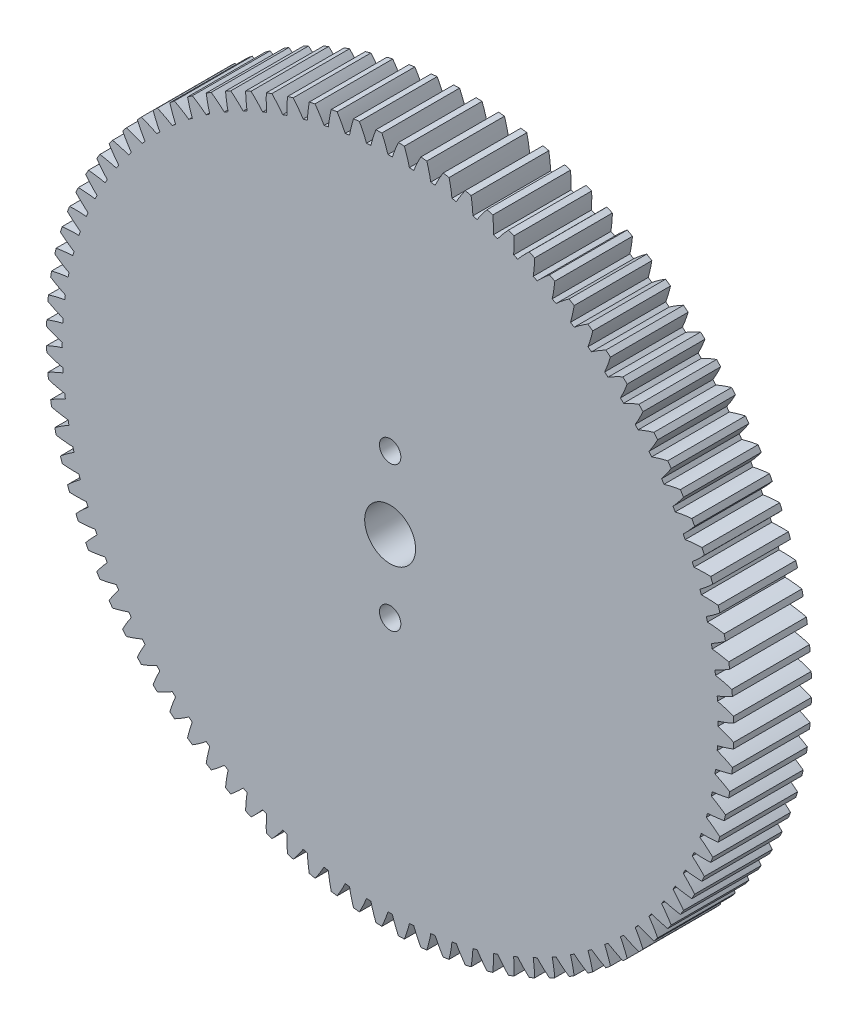
SolidWorks part; units mm, degrees
ref_plane "Front Plane" through (0, 0, 0) normal (0, 0, 1) x (1, 0, 0)
ref_plane "Top Plane" through (0, 0, 0) normal (0, 1, 0) x (1, 0, 0)
ref_plane "Right Plane" through (0, 0, 0) normal (1, 0, 0) x (0, 0, -1)
sketch "Model" plane through (0, 0, 0) normal (0, 0, 1) x (1, 0, 0)
  arc A0 (41.8739, 5.2281) -> (41.8002, 5.7878) centre (0, 0) ccw
  arc A1 (41.8002, 5.7878) -> (43.6952, 6.8252) centre (34.4061, 21.5441) ccw
  arc A2 (43.6952, 6.8252) -> (43.5702, 7.5824) centre (0, 0) ccw
  circle A387 centre (0, -9.3) radius 1.375
  circle A388 centre (0, 9.3) radius 1.375
  circle A389 centre (0, 0) radius 3.275
  arc A390 (43.5702, 7.5824) -> (41.4423, 7.9556) centre (39.5053, -9.3413) ccw
  arc A391 (41.4423, 7.9556) -> (41.3322, 8.5093) centre (0, 0) ccw
  arc A392 (41.3322, 8.5093) -> (43.1552, 9.6684) centre (32.9234, 23.7483) ccw
  arc A393 (43.1552, 9.6684) -> (42.981, 10.4158) centre (0, 0) ccw
  arc A394 (42.981, 10.4158) -> (40.8333, 10.649) centre (40.0317, -6.7375) ccw
  arc A395 (40.8333, 10.649) -> (40.6871, 11.1943) centre (0, 0) ccw
  arc A396 (40.6871, 11.1943) -> (42.4305, 12.4702) centre (31.2997, 25.8507) ccw
  arc A397 (42.4305, 12.4702) -> (42.2077, 13.2046) centre (0, 0) ccw
  arc A398 (42.2077, 13.2046) -> (40.0493, 13.2968) centre (40.3866, -4.1049) ccw
  arc A399 (40.0493, 13.2968) -> (39.8679, 13.8314) centre (0, 0) ccw
  arc A400 (39.8679, 13.8314) -> (41.5241, 15.2185) centre (29.542, 27.8425) ccw
  arc A401 (41.5241, 15.2185) -> (41.2537, 15.9368) centre (0, 0) ccw
  arc A402 (41.2537, 15.9368) -> (39.0939, 15.8877) centre (40.5686, -1.4547) ccw
  arc A403 (39.0939, 15.8877) -> (38.8779, 16.4093) centre (0, 0) ccw
  arc A404 (38.8779, 16.4093) -> (40.4398, 17.9018) centre (27.6577, 29.715) ccw
  arc A405 (40.4398, 17.9018) -> (40.1231, 18.6008) centre (0, 0) ccw
  arc A406 (40.1231, 18.6008) -> (37.9711, 18.4106) centre (40.5769, 1.2017) ccw
  arc A407 (37.9711, 18.4106) -> (37.7214, 18.9169) centre (0, 0) ccw
  arc A408 (37.7214, 18.9169) -> (39.1824, 20.5083) centre (25.6551, 31.4603) ccw
  arc A409 (39.1824, 20.5083) -> (38.8206, 21.1852) centre (0, 0) ccw
  arc A410 (38.8206, 21.1852) -> (36.6857, 20.8546) centre (40.4115, 3.853) ccw
  arc A411 (36.6857, 20.8546) -> (36.4034, 21.3435) centre (0, 0) ccw
  arc A412 (36.4034, 21.3435) -> (37.7572, 23.0271) centre (23.5425, 33.0708) ccw
  arc A413 (37.7572, 23.0271) -> (37.3519, 23.6788) centre (0, 0) ccw
  arc A414 (37.3519, 23.6788) -> (35.2432, 23.2093) centre (40.0729, 6.4878) ccw
  arc A415 (35.2432, 23.2093) -> (34.9296, 23.6787) centre (0, 0) ccw
  arc A416 (34.9296, 23.6787) -> (36.1703, 25.4472) centre (21.3292, 34.5398) ccw
  arc A417 (36.1703, 25.4472) -> (35.7233, 26.071) centre (0, 0) ccw
  arc A418 (35.7233, 26.071) -> (33.6498, 25.4646) centre (39.5628, 9.0948) ccw
  arc A419 (33.6498, 25.4646) -> (33.3061, 25.9125) centre (0, 0) ccw
  arc A420 (33.3061, 25.9125) -> (34.4285, 27.7584) centre (19.0245, 35.8608) ccw
  arc A421 (34.4285, 27.7584) -> (33.9417, 28.3516) centre (0, 0) ccw
  arc A422 (33.9417, 28.3516) -> (31.9123, 27.6109) centre (38.8833, 11.6629) ccw
  arc A423 (31.9123, 27.6109) -> (31.5401, 28.0353) centre (0, 0) ccw
  arc A424 (31.5401, 28.0353) -> (32.5393, 29.9507) centre (16.6384, 37.0283) ccw
  arc A425 (32.5393, 29.9507) -> (32.0147, 30.5108) centre (0, 0) ccw
  arc A426 (32.0147, 30.5108) -> (30.0381, 29.6389) centre (38.0372, 14.181) ccw
  arc A427 (30.0381, 29.6389) -> (29.6389, 30.0381) centre (0, 0) ccw
  arc A428 (29.6389, 30.0381) -> (30.5108, 32.0147) centre (14.181, 38.0372) ccw
  arc A429 (30.5108, 32.0147) -> (29.9507, 32.5393) centre (0, 0) ccw
  arc A430 (29.9507, 32.5393) -> (28.0353, 31.5401) centre (37.0283, 16.6384) ccw
  arc A431 (28.0353, 31.5401) -> (27.6109, 31.9123) centre (0, 0) ccw
  arc A432 (27.6109, 31.9123) -> (28.3516, 33.9417) centre (11.6629, 38.8833) ccw
  arc A433 (28.3516, 33.9417) -> (27.7584, 34.4285) centre (0, 0) ccw
  arc A434 (27.7584, 34.4285) -> (25.9125, 33.3061) centre (35.8608, 19.0245) ccw
  arc A435 (25.9125, 33.3061) -> (25.4646, 33.6498) centre (0, 0) ccw
  arc A436 (25.4646, 33.6498) -> (26.071, 35.7233) centre (9.0948, 39.5628) ccw
  arc A437 (26.071, 35.7233) -> (25.4472, 36.1703) centre (0, 0) ccw
  arc A438 (25.4472, 36.1703) -> (23.6787, 34.9296) centre (34.5398, 21.3292) ccw
  arc A439 (23.6787, 34.9296) -> (23.2093, 35.2432) centre (0, 0) ccw
  arc A440 (23.2093, 35.2432) -> (23.6788, 37.3519) centre (6.4878, 40.0729) ccw
  arc A441 (23.6788, 37.3519) -> (23.0271, 37.7572) centre (0, 0) ccw
  arc A442 (23.0271, 37.7572) -> (21.3435, 36.4034) centre (33.0708, 23.5425) ccw
  arc A443 (21.3435, 36.4034) -> (20.8546, 36.6857) centre (0, 0) ccw
  arc A444 (20.8546, 36.6857) -> (21.1852, 38.8206) centre (3.853, 40.4115) ccw
  arc A445 (21.1852, 38.8206) -> (20.5083, 39.1824) centre (0, 0) ccw
  arc A446 (20.5083, 39.1824) -> (18.9169, 37.7214) centre (31.4603, 25.6551) ccw
  arc A447 (18.9169, 37.7214) -> (18.4106, 37.9711) centre (0, 0) ccw
  arc A448 (18.4106, 37.9711) -> (18.6008, 40.1231) centre (1.2017, 40.5769) ccw
  arc A449 (18.6008, 40.1231) -> (17.9018, 40.4398) centre (0, 0) ccw
  arc A450 (17.9018, 40.4398) -> (16.4093, 38.8779) centre (29.715, 27.6577) ccw
  arc A451 (16.4093, 38.8779) -> (15.8877, 39.0939) centre (0, 0) ccw
  arc A452 (15.8877, 39.0939) -> (15.9368, 41.2537) centre (-1.4547, 40.5686) ccw
  arc A453 (15.9368, 41.2537) -> (15.2185, 41.5241) centre (0, 0) ccw
  arc A454 (15.2185, 41.5241) -> (13.8314, 39.8679) centre (27.8425, 29.542) ccw
  arc A455 (13.8314, 39.8679) -> (13.2968, 40.0493) centre (0, 0) ccw
  arc A456 (13.2968, 40.0493) -> (13.2046, 42.2077) centre (-4.1049, 40.3866) ccw
  arc A457 (13.2046, 42.2077) -> (12.4702, 42.4305) centre (0, 0) ccw
  arc A458 (12.4702, 42.4305) -> (11.1943, 40.6871) centre (25.8507, 31.2997) ccw
  arc A459 (11.1943, 40.6871) -> (10.649, 40.8333) centre (0, 0) ccw
  arc A460 (10.649, 40.8333) -> (10.4158, 42.981) centre (-6.7375, 40.0317) ccw
  arc A461 (10.4158, 42.981) -> (9.6684, 43.1552) centre (0, 0) ccw
  arc A462 (9.6684, 43.1552) -> (8.5093, 41.3322) centre (23.7483, 32.9234) ccw
  arc A463 (8.5093, 41.3322) -> (7.9556, 41.4423) centre (0, 0) ccw
  arc A464 (7.9556, 41.4423) -> (7.5824, 43.5702) centre (-9.3413, 39.5053) ccw
  arc A465 (7.5824, 43.5702) -> (6.8252, 43.6952) centre (0, 0) ccw
  arc A466 (6.8252, 43.6952) -> (5.7878, 41.8002) centre (21.5441, 34.4061) ccw
  arc A467 (5.7878, 41.8002) -> (5.2281, 41.8739) centre (0, 0) ccw
  arc A468 (5.2281, 41.8739) -> (4.7165, 43.9728) centre (-11.9051, 38.8098) ccw
  arc A469 (4.7165, 43.9728) -> (3.9528, 44.048) centre (0, 0) ccw
  arc A470 (3.9528, 44.048) -> (3.0416, 42.0892) centre (19.2477, 35.7415) ccw
  arc A471 (3.0416, 42.0892) -> (2.4782, 42.1262) centre (0, 0) ccw
  arc A472 (2.4782, 42.1262) -> (1.8305, 44.1871) centre (-14.4179, 37.9481) ccw
  arc A473 (1.8305, 44.1871) -> (1.0634, 44.2122) centre (0, 0) ccw
  arc A474 (1.0634, 44.2122) -> (0.2823, 42.1981) centre (16.8689, 36.9239) ccw
  arc A475 (0.2823, 42.1981) -> (-0.2823, 42.1981) centre (0, 0) ccw
  arc A476 (-0.2823, 42.1981) -> (-1.0634, 44.2122) centre (-16.8689, 36.9239) ccw
  arc A477 (-1.0634, 44.2122) -> (-1.8305, 44.1871) centre (0, 0) ccw
  arc A478 (-1.8305, 44.1871) -> (-2.4782, 42.1262) centre (14.4179, 37.9481) ccw
  arc A479 (-2.4782, 42.1262) -> (-3.0416, 42.0892) centre (0, 0) ccw
  arc A480 (-3.0416, 42.0892) -> (-3.9528, 44.048) centre (-19.2477, 35.7415) ccw
  arc A481 (-3.9528, 44.048) -> (-4.7165, 43.9728) centre (0, 0) ccw
  arc A482 (-4.7165, 43.9728) -> (-5.2281, 41.8739) centre (11.9051, 38.8098) ccw
  arc A483 (-5.2281, 41.8739) -> (-5.7878, 41.8002) centre (0, 0) ccw
  arc A484 (-5.7878, 41.8002) -> (-6.8252, 43.6952) centre (-21.5441, 34.4061) ccw
  arc A485 (-6.8252, 43.6952) -> (-7.5824, 43.5702) centre (0, 0) ccw
  arc A486 (-7.5824, 43.5702) -> (-7.9556, 41.4423) centre (9.3413, 39.5053) ccw
  arc A487 (-7.9556, 41.4423) -> (-8.5093, 41.3322) centre (0, 0) ccw
  arc A488 (-8.5093, 41.3322) -> (-9.6684, 43.1552) centre (-23.7483, 32.9234) ccw
  arc A489 (-9.6684, 43.1552) -> (-10.4158, 42.981) centre (0, 0) ccw
  arc A490 (-10.4158, 42.981) -> (-10.649, 40.8333) centre (6.7375, 40.0317) ccw
  arc A491 (-10.649, 40.8333) -> (-11.1943, 40.6871) centre (0, 0) ccw
  arc A492 (-11.1943, 40.6871) -> (-12.4702, 42.4305) centre (-25.8507, 31.2997) ccw
  arc A493 (-12.4702, 42.4305) -> (-13.2046, 42.2077) centre (0, 0) ccw
  arc A494 (-13.2046, 42.2077) -> (-13.2968, 40.0493) centre (4.1049, 40.3866) ccw
  arc A495 (-13.2968, 40.0493) -> (-13.8314, 39.8679) centre (0, 0) ccw
  arc A496 (-13.8314, 39.8679) -> (-15.2185, 41.5241) centre (-27.8425, 29.542) ccw
  arc A497 (-15.2185, 41.5241) -> (-15.9368, 41.2537) centre (0, 0) ccw
  arc A498 (-15.9368, 41.2537) -> (-15.8877, 39.0939) centre (1.4547, 40.5686) ccw
  arc A499 (-15.8877, 39.0939) -> (-16.4093, 38.8779) centre (0, 0) ccw
  arc A500 (-16.4093, 38.8779) -> (-17.9018, 40.4398) centre (-29.715, 27.6577) ccw
  arc A501 (-17.9018, 40.4398) -> (-18.6008, 40.1231) centre (0, 0) ccw
  arc A502 (-18.6008, 40.1231) -> (-18.4106, 37.9711) centre (-1.2017, 40.5769) ccw
  arc A503 (-18.4106, 37.9711) -> (-18.9169, 37.7214) centre (0, 0) ccw
  arc A504 (-18.9169, 37.7214) -> (-20.5083, 39.1824) centre (-31.4603, 25.6551) ccw
  arc A505 (-20.5083, 39.1824) -> (-21.1852, 38.8206) centre (0, 0) ccw
  arc A506 (-21.1852, 38.8206) -> (-20.8546, 36.6857) centre (-3.853, 40.4115) ccw
  arc A507 (-20.8546, 36.6857) -> (-21.3435, 36.4034) centre (0, 0) ccw
  arc A508 (-21.3435, 36.4034) -> (-23.0271, 37.7572) centre (-33.0708, 23.5425) ccw
  arc A509 (-23.0271, 37.7572) -> (-23.6788, 37.3519) centre (0, 0) ccw
  arc A510 (-23.6788, 37.3519) -> (-23.2093, 35.2432) centre (-6.4878, 40.0729) ccw
  arc A511 (-23.2093, 35.2432) -> (-23.6787, 34.9296) centre (0, 0) ccw
  arc A512 (-23.6787, 34.9296) -> (-25.4472, 36.1703) centre (-34.5398, 21.3292) ccw
  arc A513 (-25.4472, 36.1703) -> (-26.071, 35.7233) centre (0, 0) ccw
  arc A514 (-26.071, 35.7233) -> (-25.4646, 33.6498) centre (-9.0948, 39.5628) ccw
  arc A515 (-25.4646, 33.6498) -> (-25.9125, 33.3061) centre (0, 0) ccw
  arc A516 (-25.9125, 33.3061) -> (-27.7584, 34.4285) centre (-35.8608, 19.0245) ccw
  arc A517 (-27.7584, 34.4285) -> (-28.3516, 33.9417) centre (0, 0) ccw
  arc A518 (-28.3516, 33.9417) -> (-27.6109, 31.9123) centre (-11.6629, 38.8833) ccw
  arc A519 (-27.6109, 31.9123) -> (-28.0353, 31.5401) centre (0, 0) ccw
  arc A520 (-28.0353, 31.5401) -> (-29.9507, 32.5393) centre (-37.0283, 16.6384) ccw
  arc A521 (-29.9507, 32.5393) -> (-30.5108, 32.0147) centre (0, 0) ccw
  arc A522 (-30.5108, 32.0147) -> (-29.6389, 30.0381) centre (-14.181, 38.0372) ccw
  arc A523 (-29.6389, 30.0381) -> (-30.0381, 29.6389) centre (0, 0) ccw
  arc A524 (-30.0381, 29.6389) -> (-32.0147, 30.5108) centre (-38.0372, 14.181) ccw
  arc A525 (-32.0147, 30.5108) -> (-32.5393, 29.9507) centre (0, 0) ccw
  arc A526 (-32.5393, 29.9507) -> (-31.5401, 28.0353) centre (-16.6384, 37.0283) ccw
  arc A527 (-31.5401, 28.0353) -> (-31.9123, 27.6109) centre (0, 0) ccw
  arc A528 (-31.9123, 27.6109) -> (-33.9417, 28.3516) centre (-38.8833, 11.6629) ccw
  arc A529 (-33.9417, 28.3516) -> (-34.4285, 27.7584) centre (0, 0) ccw
  arc A530 (-34.4285, 27.7584) -> (-33.3061, 25.9125) centre (-19.0245, 35.8608) ccw
  arc A531 (-33.3061, 25.9125) -> (-33.6498, 25.4646) centre (0, 0) ccw
  arc A532 (-33.6498, 25.4646) -> (-35.7233, 26.071) centre (-39.5628, 9.0948) ccw
  arc A533 (-35.7233, 26.071) -> (-36.1703, 25.4472) centre (0, 0) ccw
  arc A534 (-36.1703, 25.4472) -> (-34.9296, 23.6787) centre (-21.3292, 34.5398) ccw
  arc A535 (-34.9296, 23.6787) -> (-35.2432, 23.2093) centre (0, 0) ccw
  arc A536 (-35.2432, 23.2093) -> (-37.3519, 23.6788) centre (-40.0729, 6.4878) ccw
  arc A537 (-37.3519, 23.6788) -> (-37.7572, 23.0271) centre (0, 0) ccw
  arc A538 (-37.7572, 23.0271) -> (-36.4034, 21.3435) centre (-23.5425, 33.0708) ccw
  arc A539 (-36.4034, 21.3435) -> (-36.6857, 20.8546) centre (0, 0) ccw
  arc A540 (-36.6857, 20.8546) -> (-38.8206, 21.1852) centre (-40.4115, 3.853) ccw
  arc A541 (-38.8206, 21.1852) -> (-39.1824, 20.5083) centre (0, 0) ccw
  arc A542 (-39.1824, 20.5083) -> (-37.7214, 18.9169) centre (-25.6551, 31.4603) ccw
  arc A543 (-37.7214, 18.9169) -> (-37.9711, 18.4106) centre (0, 0) ccw
  arc A544 (-37.9711, 18.4106) -> (-40.1231, 18.6008) centre (-40.5769, 1.2017) ccw
  arc A545 (-40.1231, 18.6008) -> (-40.4398, 17.9018) centre (0, 0) ccw
  arc A546 (-40.4398, 17.9018) -> (-38.8779, 16.4093) centre (-27.6577, 29.715) ccw
  arc A547 (-38.8779, 16.4093) -> (-39.0939, 15.8877) centre (0, 0) ccw
  arc A548 (-39.0939, 15.8877) -> (-41.2537, 15.9368) centre (-40.5686, -1.4547) ccw
  arc A549 (-41.2537, 15.9368) -> (-41.5241, 15.2185) centre (0, 0) ccw
  arc A550 (-41.5241, 15.2185) -> (-39.8679, 13.8314) centre (-29.542, 27.8425) ccw
  arc A551 (-39.8679, 13.8314) -> (-40.0493, 13.2968) centre (0, 0) ccw
  arc A552 (-40.0493, 13.2968) -> (-42.2077, 13.2046) centre (-40.3866, -4.1049) ccw
  arc A553 (-42.2077, 13.2046) -> (-42.4305, 12.4702) centre (0, 0) ccw
  arc A554 (-42.4305, 12.4702) -> (-40.6871, 11.1943) centre (-31.2997, 25.8507) ccw
  arc A555 (-40.6871, 11.1943) -> (-40.8333, 10.649) centre (0, 0) ccw
  arc A556 (-40.8333, 10.649) -> (-42.981, 10.4158) centre (-40.0317, -6.7375) ccw
  arc A557 (-42.981, 10.4158) -> (-43.1552, 9.6684) centre (0, 0) ccw
  arc A558 (-43.1552, 9.6684) -> (-41.3322, 8.5093) centre (-32.9234, 23.7483) ccw
  arc A559 (-41.3322, 8.5093) -> (-41.4423, 7.9556) centre (0, 0) ccw
  arc A560 (-41.4423, 7.9556) -> (-43.5702, 7.5824) centre (-39.5053, -9.3413) ccw
  arc A561 (-43.5702, 7.5824) -> (-43.6952, 6.8252) centre (0, 0) ccw
  arc A562 (-43.6952, 6.8252) -> (-41.8002, 5.7878) centre (-34.4061, 21.5441) ccw
  arc A563 (-41.8002, 5.7878) -> (-41.8739, 5.2281) centre (0, 0) ccw
  arc A564 (-41.8739, 5.2281) -> (-43.9728, 4.7165) centre (-38.8098, -11.9051) ccw
  arc A565 (-43.9728, 4.7165) -> (-44.048, 3.9528) centre (0, 0) ccw
  arc A566 (-44.048, 3.9528) -> (-42.0892, 3.0416) centre (-35.7415, 19.2477) ccw
  arc A567 (-42.0892, 3.0416) -> (-42.1262, 2.4782) centre (0, 0) ccw
  arc A568 (-42.1262, 2.4782) -> (-44.1871, 1.8305) centre (-37.9481, -14.4179) ccw
  arc A569 (-44.1871, 1.8305) -> (-44.2122, 1.0634) centre (0, 0) ccw
  arc A570 (-44.2122, 1.0634) -> (-42.1981, 0.2823) centre (-36.9239, 16.8689) ccw
  arc A571 (-42.1981, 0.2823) -> (-42.1981, -0.2823) centre (0, 0) ccw
  arc A572 (-42.1981, -0.2823) -> (-44.2122, -1.0634) centre (-36.9239, -16.8689) ccw
  arc A573 (-44.2122, -1.0634) -> (-44.1871, -1.8305) centre (0, 0) ccw
  arc A574 (-44.1871, -1.8305) -> (-42.1262, -2.4782) centre (-37.9481, 14.4179) ccw
  arc A575 (-42.1262, -2.4782) -> (-42.0892, -3.0416) centre (0, 0) ccw
  arc A576 (-42.0892, -3.0416) -> (-44.048, -3.9528) centre (-35.7415, -19.2477) ccw
  arc A577 (-44.048, -3.9528) -> (-43.9728, -4.7165) centre (0, 0) ccw
  arc A578 (-43.9728, -4.7165) -> (-41.8739, -5.2281) centre (-38.8098, 11.9051) ccw
  arc A579 (-41.8739, -5.2281) -> (-41.8002, -5.7878) centre (0, 0) ccw
  arc A580 (-41.8002, -5.7878) -> (-43.6952, -6.8252) centre (-34.4061, -21.5441) ccw
  arc A581 (-43.6952, -6.8252) -> (-43.5702, -7.5824) centre (0, 0) ccw
  arc A582 (-43.5702, -7.5824) -> (-41.4423, -7.9556) centre (-39.5053, 9.3413) ccw
  arc A583 (-41.4423, -7.9556) -> (-41.3322, -8.5093) centre (0, 0) ccw
  arc A584 (-41.3322, -8.5093) -> (-43.1552, -9.6684) centre (-32.9234, -23.7483) ccw
  arc A585 (-43.1552, -9.6684) -> (-42.981, -10.4158) centre (0, 0) ccw
  arc A586 (-42.981, -10.4158) -> (-40.8333, -10.649) centre (-40.0317, 6.7375) ccw
  arc A587 (-40.8333, -10.649) -> (-40.6871, -11.1943) centre (0, 0) ccw
  arc A588 (-40.6871, -11.1943) -> (-42.4305, -12.4702) centre (-31.2997, -25.8507) ccw
  arc A589 (-42.4305, -12.4702) -> (-42.2077, -13.2046) centre (0, 0) ccw
  arc A590 (-42.2077, -13.2046) -> (-40.0493, -13.2968) centre (-40.3866, 4.1049) ccw
  arc A591 (-40.0493, -13.2968) -> (-39.8679, -13.8314) centre (0, 0) ccw
  arc A592 (-39.8679, -13.8314) -> (-41.5241, -15.2185) centre (-29.542, -27.8425) ccw
  arc A593 (-41.5241, -15.2185) -> (-41.2537, -15.9368) centre (0, 0) ccw
  arc A594 (-41.2537, -15.9368) -> (-39.0939, -15.8877) centre (-40.5686, 1.4547) ccw
  arc A595 (-39.0939, -15.8877) -> (-38.8779, -16.4093) centre (0, 0) ccw
  arc A596 (-38.8779, -16.4093) -> (-40.4398, -17.9018) centre (-27.6577, -29.715) ccw
  arc A597 (-40.4398, -17.9018) -> (-40.1231, -18.6008) centre (0, 0) ccw
  arc A598 (-40.1231, -18.6008) -> (-37.9711, -18.4106) centre (-40.5769, -1.2017) ccw
  arc A599 (-37.9711, -18.4106) -> (-37.7214, -18.9169) centre (0, 0) ccw
  arc A600 (-37.7214, -18.9169) -> (-39.1824, -20.5083) centre (-25.6551, -31.4603) ccw
  arc A601 (-39.1824, -20.5083) -> (-38.8206, -21.1852) centre (0, 0) ccw
  arc A602 (-38.8206, -21.1852) -> (-36.6857, -20.8546) centre (-40.4115, -3.853) ccw
  arc A603 (-36.6857, -20.8546) -> (-36.4034, -21.3435) centre (0, 0) ccw
  arc A604 (-36.4034, -21.3435) -> (-37.7572, -23.0271) centre (-23.5425, -33.0708) ccw
  arc A605 (-37.7572, -23.0271) -> (-37.3519, -23.6788) centre (0, 0) ccw
  arc A606 (-37.3519, -23.6788) -> (-35.2432, -23.2093) centre (-40.0729, -6.4878) ccw
  arc A607 (-35.2432, -23.2093) -> (-34.9296, -23.6787) centre (0, 0) ccw
  arc A608 (-34.9296, -23.6787) -> (-36.1703, -25.4472) centre (-21.3292, -34.5398) ccw
  arc A609 (-36.1703, -25.4472) -> (-35.7233, -26.071) centre (0, 0) ccw
  arc A610 (-35.7233, -26.071) -> (-33.6498, -25.4646) centre (-39.5628, -9.0948) ccw
  arc A611 (-33.6498, -25.4646) -> (-33.3061, -25.9125) centre (0, 0) ccw
  arc A612 (-33.3061, -25.9125) -> (-34.4285, -27.7584) centre (-19.0245, -35.8608) ccw
  arc A613 (-34.4285, -27.7584) -> (-33.9417, -28.3516) centre (0, 0) ccw
  arc A614 (-33.9417, -28.3516) -> (-31.9123, -27.6109) centre (-38.8833, -11.6629) ccw
  arc A615 (-31.9123, -27.6109) -> (-31.5401, -28.0353) centre (0, 0) ccw
  arc A616 (-31.5401, -28.0353) -> (-32.5393, -29.9507) centre (-16.6384, -37.0283) ccw
  arc A617 (-32.5393, -29.9507) -> (-32.0147, -30.5108) centre (0, 0) ccw
  arc A618 (-32.0147, -30.5108) -> (-30.0381, -29.6389) centre (-38.0372, -14.181) ccw
  arc A619 (-30.0381, -29.6389) -> (-29.6389, -30.0381) centre (0, 0) ccw
  arc A620 (-29.6389, -30.0381) -> (-30.5108, -32.0147) centre (-14.181, -38.0372) ccw
  arc A621 (-30.5108, -32.0147) -> (-29.9507, -32.5393) centre (0, 0) ccw
  arc A622 (-29.9507, -32.5393) -> (-28.0353, -31.5401) centre (-37.0283, -16.6384) ccw
  arc A623 (-28.0353, -31.5401) -> (-27.6109, -31.9123) centre (0, 0) ccw
  arc A624 (-27.6109, -31.9123) -> (-28.3516, -33.9417) centre (-11.6629, -38.8833) ccw
  arc A625 (-28.3516, -33.9417) -> (-27.7584, -34.4285) centre (0, 0) ccw
  arc A626 (-27.7584, -34.4285) -> (-25.9125, -33.3061) centre (-35.8608, -19.0245) ccw
  arc A627 (-25.9125, -33.3061) -> (-25.4646, -33.6498) centre (0, 0) ccw
  arc A628 (-25.4646, -33.6498) -> (-26.071, -35.7233) centre (-9.0948, -39.5628) ccw
  arc A629 (-26.071, -35.7233) -> (-25.4472, -36.1703) centre (0, 0) ccw
  arc A630 (-25.4472, -36.1703) -> (-23.6787, -34.9296) centre (-34.5398, -21.3292) ccw
  arc A631 (-23.6787, -34.9296) -> (-23.2093, -35.2432) centre (0, 0) ccw
  arc A632 (-23.2093, -35.2432) -> (-23.6788, -37.3519) centre (-6.4878, -40.0729) ccw
  arc A633 (-23.6788, -37.3519) -> (-23.0271, -37.7572) centre (0, 0) ccw
  arc A634 (-23.0271, -37.7572) -> (-21.3435, -36.4034) centre (-33.0708, -23.5425) ccw
  arc A635 (-21.3435, -36.4034) -> (-20.8546, -36.6857) centre (0, 0) ccw
  arc A636 (-20.8546, -36.6857) -> (-21.1852, -38.8206) centre (-3.853, -40.4115) ccw
  arc A637 (-21.1852, -38.8206) -> (-20.5083, -39.1824) centre (0, 0) ccw
  arc A638 (-20.5083, -39.1824) -> (-18.9169, -37.7214) centre (-31.4603, -25.6551) ccw
  arc A639 (-18.9169, -37.7214) -> (-18.4106, -37.9711) centre (0, 0) ccw
  arc A640 (-18.4106, -37.9711) -> (-18.6008, -40.1231) centre (-1.2017, -40.5769) ccw
  arc A641 (-18.6008, -40.1231) -> (-17.9018, -40.4398) centre (0, 0) ccw
  arc A642 (-17.9018, -40.4398) -> (-16.4093, -38.8779) centre (-29.715, -27.6577) ccw
  arc A643 (-16.4093, -38.8779) -> (-15.8877, -39.0939) centre (0, 0) ccw
  arc A644 (-15.8877, -39.0939) -> (-15.9368, -41.2537) centre (1.4547, -40.5686) ccw
  arc A645 (-15.9368, -41.2537) -> (-15.2185, -41.5241) centre (0, 0) ccw
  arc A646 (-15.2185, -41.5241) -> (-13.8314, -39.8679) centre (-27.8425, -29.542) ccw
  arc A647 (-13.8314, -39.8679) -> (-13.2968, -40.0493) centre (0, 0) ccw
  arc A648 (-13.2968, -40.0493) -> (-13.2046, -42.2077) centre (4.1049, -40.3866) ccw
  arc A649 (-13.2046, -42.2077) -> (-12.4702, -42.4305) centre (0, 0) ccw
  arc A650 (-12.4702, -42.4305) -> (-11.1943, -40.6871) centre (-25.8507, -31.2997) ccw
  arc A651 (-11.1943, -40.6871) -> (-10.649, -40.8333) centre (0, 0) ccw
  arc A652 (-10.649, -40.8333) -> (-10.4158, -42.981) centre (6.7375, -40.0317) ccw
  arc A653 (-10.4158, -42.981) -> (-9.6684, -43.1552) centre (0, 0) ccw
  arc A654 (-9.6684, -43.1552) -> (-8.5093, -41.3322) centre (-23.7483, -32.9234) ccw
  arc A655 (-8.5093, -41.3322) -> (-7.9556, -41.4423) centre (0, 0) ccw
  arc A656 (-7.9556, -41.4423) -> (-7.5824, -43.5702) centre (9.3413, -39.5053) ccw
  arc A657 (-7.5824, -43.5702) -> (-6.8252, -43.6952) centre (0, 0) ccw
  arc A658 (-6.8252, -43.6952) -> (-5.7878, -41.8002) centre (-21.5441, -34.4061) ccw
  arc A659 (-5.7878, -41.8002) -> (-5.2281, -41.8739) centre (0, 0) ccw
  arc A660 (-5.2281, -41.8739) -> (-4.7165, -43.9728) centre (11.9051, -38.8098) ccw
  arc A661 (-4.7165, -43.9728) -> (-3.9528, -44.048) centre (0, 0) ccw
  arc A662 (-3.9528, -44.048) -> (-3.0416, -42.0892) centre (-19.2477, -35.7415) ccw
  arc A663 (-3.0416, -42.0892) -> (-2.4782, -42.1262) centre (0, 0) ccw
  arc A664 (-2.4782, -42.1262) -> (-1.8305, -44.1871) centre (14.4179, -37.9481) ccw
  arc A665 (-1.8305, -44.1871) -> (-1.0634, -44.2122) centre (0, 0) ccw
  arc A666 (-1.0634, -44.2122) -> (-0.2823, -42.1981) centre (-16.8689, -36.9239) ccw
  arc A667 (-0.2823, -42.1981) -> (0.2823, -42.1981) centre (0, 0) ccw
  arc A668 (0.2823, -42.1981) -> (1.0634, -44.2122) centre (16.8689, -36.9239) ccw
  arc A669 (1.0634, -44.2122) -> (1.8305, -44.1871) centre (0, 0) ccw
  arc A670 (1.8305, -44.1871) -> (2.4782, -42.1262) centre (-14.4179, -37.9481) ccw
  arc A671 (2.4782, -42.1262) -> (3.0416, -42.0892) centre (0, 0) ccw
  arc A672 (3.0416, -42.0892) -> (3.9528, -44.048) centre (19.2477, -35.7415) ccw
  arc A673 (3.9528, -44.048) -> (4.7165, -43.9728) centre (0, 0) ccw
  arc A674 (4.7165, -43.9728) -> (5.2281, -41.8739) centre (-11.9051, -38.8098) ccw
  arc A675 (5.2281, -41.8739) -> (5.7878, -41.8002) centre (0, 0) ccw
  arc A676 (5.7878, -41.8002) -> (6.8252, -43.6952) centre (21.5441, -34.4061) ccw
  arc A677 (6.8252, -43.6952) -> (7.5824, -43.5702) centre (0, 0) ccw
  arc A678 (7.5824, -43.5702) -> (7.9556, -41.4423) centre (-9.3413, -39.5053) ccw
  arc A679 (7.9556, -41.4423) -> (8.5093, -41.3322) centre (0, 0) ccw
  arc A680 (8.5093, -41.3322) -> (9.6684, -43.1552) centre (23.7483, -32.9234) ccw
  arc A681 (9.6684, -43.1552) -> (10.4158, -42.981) centre (0, 0) ccw
  arc A682 (10.4158, -42.981) -> (10.649, -40.8333) centre (-6.7375, -40.0317) ccw
  arc A683 (10.649, -40.8333) -> (11.1943, -40.6871) centre (0, 0) ccw
  arc A684 (11.1943, -40.6871) -> (12.4702, -42.4305) centre (25.8507, -31.2997) ccw
  arc A685 (12.4702, -42.4305) -> (13.2046, -42.2077) centre (0, 0) ccw
  arc A686 (13.2046, -42.2077) -> (13.2968, -40.0493) centre (-4.1049, -40.3866) ccw
  arc A687 (13.2968, -40.0493) -> (13.8314, -39.8679) centre (0, 0) ccw
  arc A688 (13.8314, -39.8679) -> (15.2185, -41.5241) centre (27.8425, -29.542) ccw
  arc A689 (15.2185, -41.5241) -> (15.9368, -41.2537) centre (0, 0) ccw
  arc A690 (15.9368, -41.2537) -> (15.8877, -39.0939) centre (-1.4547, -40.5686) ccw
  arc A691 (15.8877, -39.0939) -> (16.4093, -38.8779) centre (0, 0) ccw
  arc A692 (16.4093, -38.8779) -> (17.9018, -40.4398) centre (29.715, -27.6577) ccw
  arc A693 (17.9018, -40.4398) -> (18.6008, -40.1231) centre (0, 0) ccw
  arc A694 (18.6008, -40.1231) -> (18.4106, -37.9711) centre (1.2017, -40.5769) ccw
  arc A695 (18.4106, -37.9711) -> (18.9169, -37.7214) centre (0, 0) ccw
  arc A696 (18.9169, -37.7214) -> (20.5083, -39.1824) centre (31.4603, -25.6551) ccw
  arc A697 (20.5083, -39.1824) -> (21.1852, -38.8206) centre (0, 0) ccw
  arc A698 (21.1852, -38.8206) -> (20.8546, -36.6857) centre (3.853, -40.4115) ccw
  arc A699 (20.8546, -36.6857) -> (21.3435, -36.4034) centre (0, 0) ccw
  arc A700 (21.3435, -36.4034) -> (23.0271, -37.7572) centre (33.0708, -23.5425) ccw
  arc A701 (23.0271, -37.7572) -> (23.6788, -37.3519) centre (0, 0) ccw
  arc A702 (23.6788, -37.3519) -> (23.2093, -35.2432) centre (6.4878, -40.0729) ccw
  arc A703 (23.2093, -35.2432) -> (23.6787, -34.9296) centre (0, 0) ccw
  arc A704 (23.6787, -34.9296) -> (25.4472, -36.1703) centre (34.5398, -21.3292) ccw
  arc A705 (25.4472, -36.1703) -> (26.071, -35.7233) centre (0, 0) ccw
  arc A706 (26.071, -35.7233) -> (25.4646, -33.6498) centre (9.0948, -39.5628) ccw
  arc A707 (25.4646, -33.6498) -> (25.9125, -33.3061) centre (0, 0) ccw
  arc A708 (25.9125, -33.3061) -> (27.7584, -34.4285) centre (35.8608, -19.0245) ccw
  arc A709 (27.7584, -34.4285) -> (28.3516, -33.9417) centre (0, 0) ccw
  arc A710 (28.3516, -33.9417) -> (27.6109, -31.9123) centre (11.6629, -38.8833) ccw
  arc A711 (27.6109, -31.9123) -> (28.0353, -31.5401) centre (0, 0) ccw
  arc A712 (28.0353, -31.5401) -> (29.9507, -32.5393) centre (37.0283, -16.6384) ccw
  arc A713 (29.9507, -32.5393) -> (30.5108, -32.0147) centre (0, 0) ccw
  arc A714 (30.5108, -32.0147) -> (29.6389, -30.0381) centre (14.181, -38.0372) ccw
  arc A715 (29.6389, -30.0381) -> (30.0381, -29.6389) centre (0, 0) ccw
  arc A716 (30.0381, -29.6389) -> (32.0147, -30.5108) centre (38.0372, -14.181) ccw
  arc A717 (32.0147, -30.5108) -> (32.5393, -29.9507) centre (0, 0) ccw
  arc A718 (32.5393, -29.9507) -> (31.5401, -28.0353) centre (16.6384, -37.0283) ccw
  arc A719 (31.5401, -28.0353) -> (31.9123, -27.6109) centre (0, 0) ccw
  arc A720 (31.9123, -27.6109) -> (33.9417, -28.3516) centre (38.8833, -11.6629) ccw
  arc A721 (33.9417, -28.3516) -> (34.4285, -27.7584) centre (0, 0) ccw
  arc A722 (34.4285, -27.7584) -> (33.3061, -25.9125) centre (19.0245, -35.8608) ccw
  arc A723 (33.3061, -25.9125) -> (33.6498, -25.4646) centre (0, 0) ccw
  arc A724 (33.6498, -25.4646) -> (35.7233, -26.071) centre (39.5628, -9.0948) ccw
  arc A725 (35.7233, -26.071) -> (36.1703, -25.4472) centre (0, 0) ccw
  arc A726 (36.1703, -25.4472) -> (34.9296, -23.6787) centre (21.3292, -34.5398) ccw
  arc A727 (34.9296, -23.6787) -> (35.2432, -23.2093) centre (0, 0) ccw
  arc A728 (35.2432, -23.2093) -> (37.3519, -23.6788) centre (40.0729, -6.4878) ccw
  arc A729 (37.3519, -23.6788) -> (37.7572, -23.0271) centre (0, 0) ccw
  arc A730 (37.7572, -23.0271) -> (36.4034, -21.3435) centre (23.5425, -33.0708) ccw
  arc A731 (36.4034, -21.3435) -> (36.6857, -20.8546) centre (0, 0) ccw
  arc A732 (36.6857, -20.8546) -> (38.8206, -21.1852) centre (40.4115, -3.853) ccw
  arc A733 (38.8206, -21.1852) -> (39.1824, -20.5083) centre (0, 0) ccw
  arc A734 (39.1824, -20.5083) -> (37.7214, -18.9169) centre (25.6551, -31.4603) ccw
  arc A735 (37.7214, -18.9169) -> (37.9711, -18.4106) centre (0, 0) ccw
  arc A736 (37.9711, -18.4106) -> (40.1231, -18.6008) centre (40.5769, -1.2017) ccw
  arc A737 (40.1231, -18.6008) -> (40.4398, -17.9018) centre (0, 0) ccw
  arc A738 (40.4398, -17.9018) -> (38.8779, -16.4093) centre (27.6577, -29.715) ccw
  arc A739 (38.8779, -16.4093) -> (39.0939, -15.8877) centre (0, 0) ccw
  arc A740 (39.0939, -15.8877) -> (41.2537, -15.9368) centre (40.5686, 1.4547) ccw
  arc A741 (41.2537, -15.9368) -> (41.5241, -15.2185) centre (0, 0) ccw
  arc A742 (41.5241, -15.2185) -> (39.8679, -13.8314) centre (29.542, -27.8425) ccw
  arc A743 (39.8679, -13.8314) -> (40.0493, -13.2968) centre (0, 0) ccw
  arc A744 (40.0493, -13.2968) -> (42.2077, -13.2046) centre (40.3866, 4.1049) ccw
  arc A745 (42.2077, -13.2046) -> (42.4305, -12.4702) centre (0, 0) ccw
  arc A746 (42.4305, -12.4702) -> (40.6871, -11.1943) centre (31.2997, -25.8507) ccw
  arc A747 (40.6871, -11.1943) -> (40.8333, -10.649) centre (0, 0) ccw
  arc A748 (40.8333, -10.649) -> (42.981, -10.4158) centre (40.0317, 6.7375) ccw
  arc A749 (42.981, -10.4158) -> (43.1552, -9.6684) centre (0, 0) ccw
  arc A750 (43.1552, -9.6684) -> (41.3322, -8.5093) centre (32.9234, -23.7483) ccw
  arc A751 (41.3322, -8.5093) -> (41.4423, -7.9556) centre (0, 0) ccw
  arc A752 (41.4423, -7.9556) -> (43.5702, -7.5824) centre (39.5053, 9.3413) ccw
  arc A753 (43.5702, -7.5824) -> (43.6952, -6.8252) centre (0, 0) ccw
  arc A754 (43.6952, -6.8252) -> (41.8002, -5.7878) centre (34.4061, -21.5441) ccw
  arc A755 (41.8002, -5.7878) -> (41.8739, -5.2281) centre (0, 0) ccw
  arc A756 (41.8739, -5.2281) -> (43.9728, -4.7165) centre (38.8098, 11.9051) ccw
  arc A757 (43.9728, -4.7165) -> (44.048, -3.9528) centre (0, 0) ccw
  arc A758 (44.048, -3.9528) -> (42.0892, -3.0416) centre (35.7415, -19.2477) ccw
  arc A759 (42.0892, -3.0416) -> (42.1262, -2.4782) centre (0, 0) ccw
  arc A760 (42.1262, -2.4782) -> (44.1871, -1.8305) centre (37.9481, 14.4179) ccw
  arc A761 (44.1871, -1.8305) -> (44.2122, -1.0634) centre (0, 0) ccw
  arc A762 (44.2122, -1.0634) -> (42.1981, -0.2823) centre (36.9239, -16.8689) ccw
  arc A763 (42.1981, -0.2823) -> (42.1981, 0.2823) centre (0, 0) ccw
  arc A764 (42.1981, 0.2823) -> (44.2122, 1.0634) centre (36.9239, 16.8689) ccw
  arc A765 (44.2122, 1.0634) -> (44.1871, 1.8305) centre (0, 0) ccw
  arc A766 (44.1871, 1.8305) -> (42.1262, 2.4782) centre (37.9481, -14.4179) ccw
  arc A767 (42.1262, 2.4782) -> (42.0892, 3.0416) centre (0, 0) ccw
  arc A768 (42.0892, 3.0416) -> (44.048, 3.9528) centre (35.7415, 19.2477) ccw
  arc A769 (44.048, 3.9528) -> (43.9728, 4.7165) centre (0, 0) ccw
  arc A770 (43.9728, 4.7165) -> (41.8739, 5.2281) centre (38.8098, -11.9051) ccw
extrude "Boss-Extrude1" add sketch "Model" along normal blind 10
